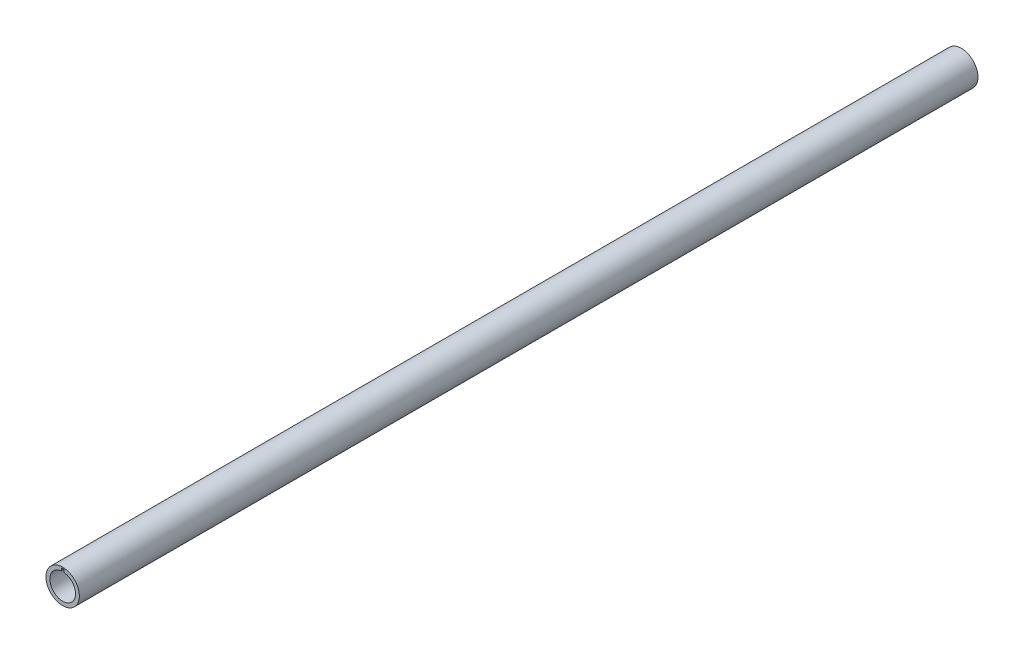
SolidWorks part; units mm, degrees
ref_plane "Front Plane" through (0, 0, 0) normal (0, 0, 1) x (1, 0, 0)
ref_plane "Top Plane" through (0, 0, 0) normal (0, 1, 0) x (1, 0, 0)
ref_plane "Right Plane" through (0, 0, 0) normal (1, 0, 0) x (0, 0, -1)
sketch "Sketch1" plane through (0, 0, 0) normal (0, 0, 1) x (1, 0, 0)
  circle A0 centre (0, 0) radius 10
  circle A1 centre (0, 0) radius 13
  dimension "D1" = 20
  dimension "D2" = 26
extrude "Boss-Extrude1" add sketch "Sketch1" along normal blind 700
sketch "Sketch2" plane through (0, 0, 700) normal (0, 0, 1) x (1, 0, 0)
  line L0 (0, 0) -> (0, 10) construction
  line L1 (0, 10) -> (-1, 10) construction
  line L4 (-1, 9.9499) -> (-1, 12)
  line L5 (-1, 12) -> (1, 12)
  line L6 (1, 9.9499) -> (1, 12)
  circle A0 centre (0, 0) radius 10 construction
  arc A1 (1, 9.9499) -> (-1, 9.9499) centre (0, 0) ccw
  dimension "D1" = 1
  dimension "D2" = 1
  dimension "D3" = 2
extrude "Cut-Extrude1" cut sketch "Sketch2" against normal blind 20
sketch "Sketch3" plane through (0, 0, 0) normal (0, 0, -1) x (-1, 0, 0)
  line L0 (0, 0) -> (0, 10) construction
  line L4 (-1, 9.9499) -> (-1, 11.9499)
  line L5 (-1, 11.9499) -> (1, 11.9499)
  line L6 (1, 9.9499) -> (1, 11.9499)
  circle A0 centre (0, 0) radius 10 construction
  arc A1 (1, 9.9499) -> (-1, 9.9499) centre (0, 0) ccw
  dimension "D1" = 2
  dimension "D2" = 2
  dimension "D3" = 1
extrude "Cut-Extrude2" cut sketch "Sketch3" against normal blind 20
